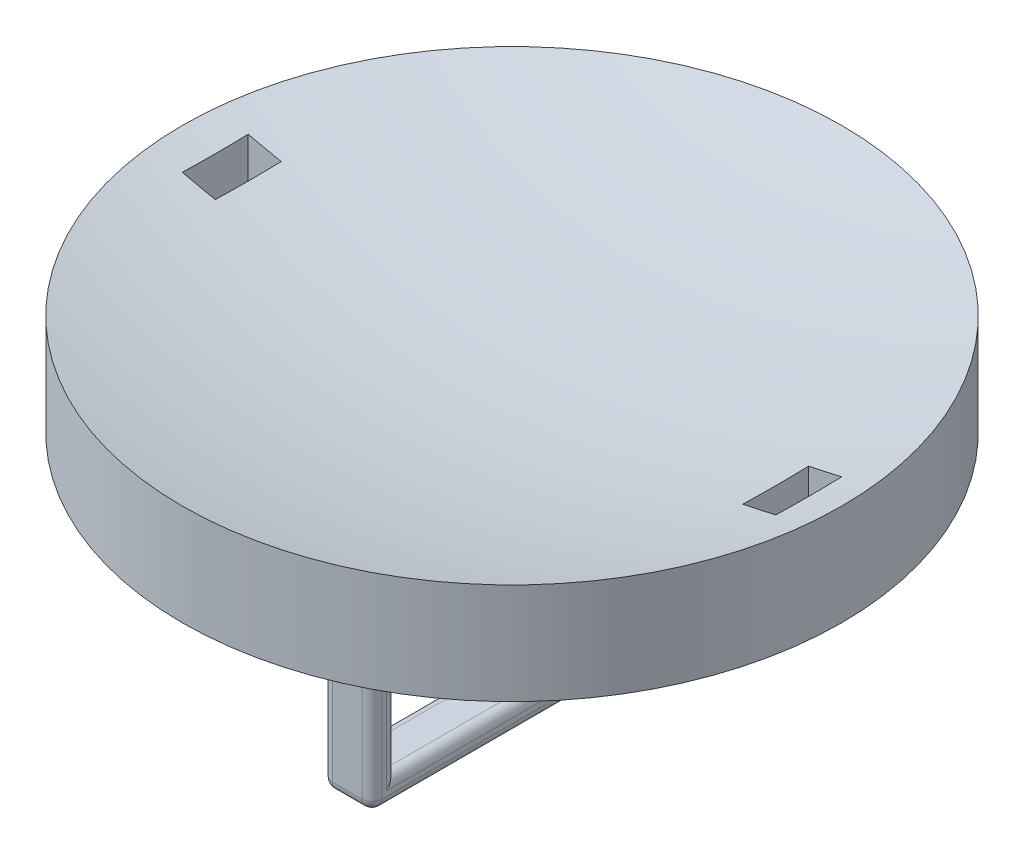
SolidWorks part; units mm, degrees
ref_plane "Plan de face" through (0, 0, 0) normal (0, 0, 1) x (1, 0, 0)
ref_plane "Plan de dessus" through (0, 0, 0) normal (0, 1, 0) x (1, 0, 0)
ref_plane "Plan de droite" through (0, 0, 0) normal (1, 0, 0) x (0, 0, -1)
sketch "Esquisse1" plane through (0, 0, 0) normal (0, 0, 1) x (1, 0, 0)
  line L0 (0, 0) -> (0, 160) construction
  line L2 (-20, -3.5908) -> (-20, 2.5403)
  line L3 (0, -5.9501) -> (0, 0)
  arc A0 (-20, 2.5403) -> (0, 0) centre (0, 80) ccw
  arc A1 (0, -5.9501) -> (-20, -3.5908) centre (0, 80) cw
  dimension "D1" = 80
  dimension "D2" = 20
revolve "Révolution3" add sketch "Esquisse1" angle 360 about L0
sketch "Esquisse2" plane through (0, 0, 0) normal (1, 0, 0) x (0, 0, -1)
  line L1 (-10, -3) -> (10, -3)
  line L2 (-10, -3) -> (-10, -18)
  line L3 (-10, -18) -> (10, -18)
  line L4 (10, -3) -> (10, -18)
  line L5 (-10, -3) -> (10, -18) construction
  line L6 (-10, -18) -> (10, -3) construction
  line L7 (-8.5, -4.5) -> (8.5, -4.5)
  line L8 (-8.5, -4.5) -> (-8.5, -16.5)
  line L9 (-8.5, -16.5) -> (8.5, -16.5)
  line L10 (8.5, -4.5) -> (8.5, -16.5)
  line L11 (-8.5, -4.5) -> (8.5, -16.5) construction
  line L12 (-8.5, -16.5) -> (8.5, -4.5) construction
  point P0 (0, -10.5)
  point P5 (0, -10.5)
  dimension "D1" = 1.5
  dimension "D2" = 1.5
  dimension "D3" = 3
  dimension "D4" = 18
  dimension "D5" = 20
extrude "Boss.-Extru.1" add sketch "Esquisse2" along normal mid plane 3
fillet "Congé4" radius 0.6 22 edges at (1.5, -5.4377, -9.2504) (-1.5, -5.4377, -9.2504) (1.5, -11.6766, -10) (0, -5.3664, -10) (-1.5, -11.6766, -10) (0, -18, 10) (1.5, -18, 0) (0, -18, -10) (-1.5, -18, 0) (0, -5.5287, -8.5) (0, -5.5287, 8.5) (0, -5.3664, 10) (1.5, -11.0078, 8.5) (1.5, -16.5, 0) (1.5, -11.0078, -8.5) (1.5, -11.6766, 10) (1.5, -5.4377, 9.2504) (-1.5, -11.0078, -8.5) (-1.5, -16.5, 0) (-1.5, -11.0078, 8.5) (-1.5, -5.4377, 9.2504) (-1.5, -11.6766, 10)
sketch "Esquisse4" plane through (0, 0, 0) normal (0, 1, 0) x (1, 0, 0)
  line L13 (-18, -2) -> (-16, -2)
  line L14 (-18, -2) -> (-18, 2)
  line L15 (-18, 2) -> (-16, 2)
  line L16 (-16, -2) -> (-16, 2)
  line L17 (-18, -2) -> (-16, 2) construction
  line L18 (-18, 2) -> (-16, -2) construction
  line L19 (16, -2) -> (18, -2)
  line L20 (16, -2) -> (16, 2)
  line L21 (16, 2) -> (18, 2)
  line L22 (18, -2) -> (18, 2)
  line L23 (16, -2) -> (18, 2) construction
  line L24 (16, 2) -> (18, -2) construction
  point P10 (17, 0)
  point P12 (-17, 0)
  dimension "D7" = 17
  dimension "D8" = 17
  dimension "D9" = 2
  dimension "D10" = 2
  dimension "D11" = 4
  dimension "D12" = 4
extrude "Enlèv. mat.-Extru.1" cut sketch "Esquisse4" against normal mid plane 32
